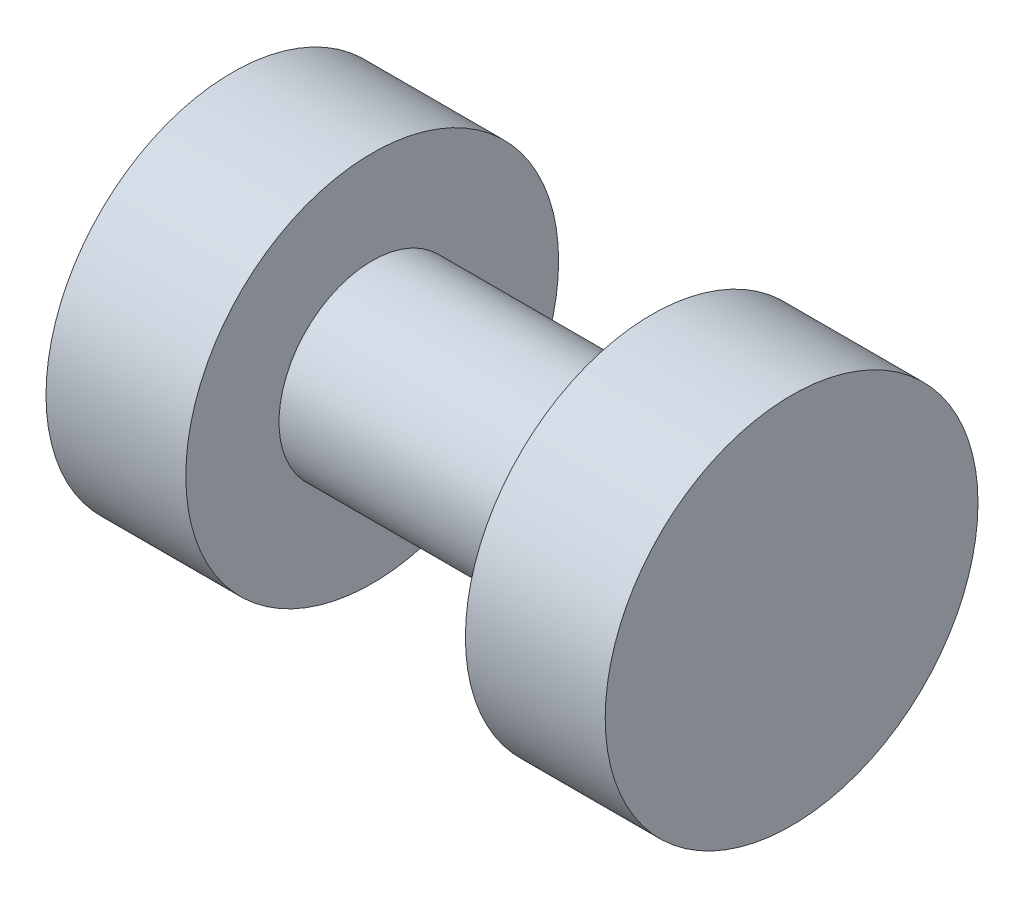
SolidWorks part; units mm, degrees
ref_plane "Alzado" through (0, 0, 0) normal (0, 0, 1) x (1, 0, 0)
ref_plane "Planta" through (0, 0, 0) normal (0, 1, 0) x (1, 0, 0)
ref_plane "Vista lateral" through (0, 0, 0) normal (1, 0, 0) x (0, 0, -1)
sketch "Croquis1" plane through (0, 0, 0) normal (0, 0, 1) x (1, 0, 0)
  line L0 (0, 0) -> (0, 10)
  line L1 (0, 10) -> (7.5, 10)
  line L2 (7.5, 10) -> (7.5, 5)
  line L3 (7.5, 5) -> (22.5, 5)
  line L4 (22.5, 5) -> (22.5, 10)
  line L5 (22.5, 10) -> (30, 10)
  line L6 (30, 10) -> (30, 0)
  line L7 (30, 0) -> (0, 0)
  dimension "D1" = 7.5
  dimension "D2" = 7.5
  dimension "D3" = 15
  dimension "D4" = 10
  dimension "D5" = 10
  dimension "D6" = 5
revolve "Revolución1" add sketch "Croquis1" angle 360 about L7
